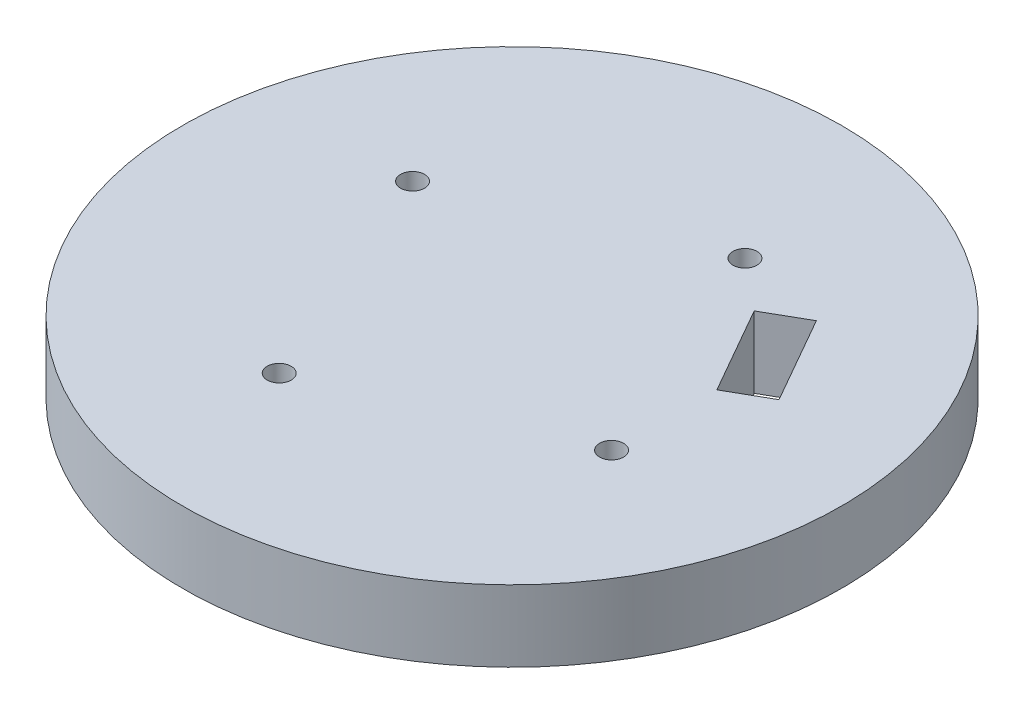
SolidWorks part; units mm, degrees
ref_plane "Alzado" through (0, 0, 0) normal (0, 0, 1) x (1, 0, 0)
ref_plane "Planta" through (0, 0, 0) normal (0, 1, 0) x (1, 0, 0)
ref_plane "Vista lateral" through (0, 0, 0) normal (1, 0, 0) x (0, 0, -1)
sketch "Croquis1" plane through (0, 0, 0) normal (0, 1, 0) x (1, 0, 0)
  circle A0 centre (0, 0) radius 27.5
  dimension "D1" = 55
extrude "Saliente-Extruir1" add sketch "Croquis1" along normal blind 20
sketch "Croquis3" plane through (0, 20, 0) normal (0, 1, 0) x (1, 0, 0)
  circle A0 centre (0, 0) radius 5.5
  dimension "D1" = 11
extrude "Cortar-Extruir1" cut sketch "Croquis3" against normal blind 10
sketch "Croquis4" plane through (0, 0, 0) normal (0, -1, 0) x (1, 0, 0)
  circle A0 centre (12.2243, -15.8293) radius 2
  circle A1 centre (-15.8293, -12.2243) radius 2
  circle A2 centre (-12.2243, 15.8293) radius 2
  circle A3 centre (15.8293, 12.2243) radius 2
  point P2 (-10.65, -10.8448)
  point P3 (12.2243, -15.8293)
  point P11 (0, 0)
  dimension "D1" = 4
  dimension "D2" = 4
extrude "Cortar-Extruir2" cut sketch "Croquis4" against normal blind 10
sketch "Croquis5" plane through (0, 20, 0) normal (0, 1, 0) x (1, 0, 0)
  circle A0 centre (0, 0) radius 60
extrude "Saliente-Extruir2" add sketch "Croquis5" along normal blind 13
sketch "Croquis6" plane through (0, 33, 0) normal (0, 1, 0) x (1, 0, 0)
  line L0 (28.4833, 26.9158) -> (21.2803, 22.8026)
  line L1 (21.2803, 22.8026) -> (30.3306, 6.9539)
  line L2 (30.3306, 6.9539) -> (37.5336, 11.0671)
  line L3 (37.5336, 11.0671) -> (28.4833, 26.9158)
extrude "Cortar-Extruir3" cut sketch "Croquis6" against normal through all
sketch "Croquis7" plane through (0, 20, 0) normal (0, -1, 0) x (1, 0, 0)
  circle A0 centre (-30.2569, -12.1418) radius 2.1865
  circle A1 centre (-12.1418, 30.2569) radius 2.1865
  circle A2 centre (30.2569, 12.1418) radius 2.1865
  circle A3 centre (12.1418, -30.2569) radius 2.1865
  point P11 (0, 0)
  dimension "D1" = 4
extrude "Cortar-Extruir4" cut sketch "Croquis7" against normal through all contours A0 | A3 | A2 | A1
